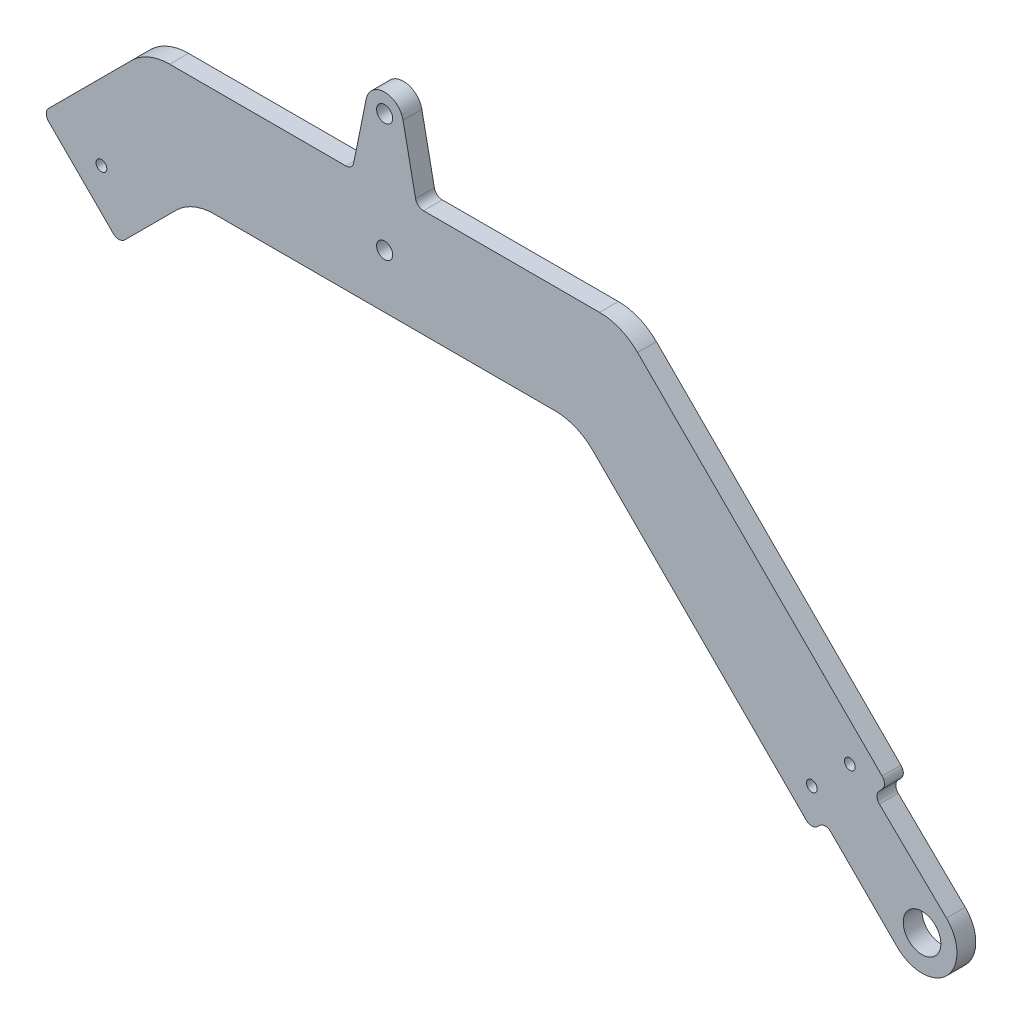
SolidWorks part; units mm, degrees
ref_plane "Front Plane" through (0, 0, 0) normal (0, 0, 1) x (1, 0, 0)
ref_plane "Top Plane" through (0, 0, 0) normal (0, 1, 0) x (1, 0, 0)
ref_plane "Right Plane" through (0, 0, 0) normal (1, 0, 0) x (0, 0, -1)
sketch "Sketch2" plane through (0, 0, 0) normal (0, 0, 1) x (1, 0, 0)
  line L0 (-100, 0) -> (100, 0) construction
  line L1 (-100, 0) -> (0, 100) construction
  line L2 (0, 100) -> (100, 0) construction
  line L3 (0, 0) -> (-52.6991, 47.3009) construction
  line L4 (-40, 60) -> (40, 60) construction
  line L5 (0, 100) -> (0, 60) construction
  circle A0 centre (-100, 0) radius 20
  circle A1 centre (0, 0) radius 20
  circle A2 centre (100, 0) radius 20
  point P2 (0, 0)
  dimension "D5" = 40
  dimension "D1" = 200
  dimension "D2" = 93.09
  dimension "D3" = 80
  dimension "D4" = 90
sketch "Sketch3" plane through (0, 0, 0) normal (0, 0, 1) x (1, 0, 0)
  line L0 (-40, 60) -> (-56.5165, 43.4835) construction
  line L1 (75.9584, 9.8995) -> (90.1005, 24.0416) construction
  line L2 (-40, 60) -> (40, 60) construction
  line L3 (40, 60) -> (86.565, 13.435) construction
  line L4 (0, 100) -> (100, 0) construction
  line L5 (86.565, 13.435) -> (40, 60) construction
  line L6 (-100, 0) -> (0, 100) construction
  line L7 (44.1421, 70) -> (93.636, 20.5061)
  line L8 (-44.1421, 70) -> (44.1421, 70)
  line L9 (-44.1421, 70) -> (-63.5876, 50.5546)
  line L10 (35.8579, 50) -> (79.4939, 6.364)
  line L11 (-35.8579, 50) -> (35.8579, 50)
  line L12 (-35.8579, 50) -> (-49.4454, 36.4124)
  line L13 (-63.5876, 50.5546) -> (-49.4454, 36.4124)
  line L14 (79.4939, 6.364) -> (93.636, 20.5061)
  line L15 (81.9688, 8.8388) -> (95.4038, -4.5962)
  line L16 (90.9809, 17.8509) -> (104.534, 4.6576)
  line L17 (-3.4304, 82.6944) -> (-6, 70)
  line L18 (0, 100) -> (0, 60) construction
  line L19 (3.4304, 82.6944) -> (6, 70)
  circle A0 centre (100, 0) radius 3.5
  circle A1 centre (100, 0) radius 10 construction
  arc A2 (95.4038, -4.5962) -> (104.534, 4.6576) centre (100, 0) ccw
  circle A3 centre (100, 0) radius 0.5
  circle A4 centre (100, 0) radius 20 construction
  circle A5 centre (100, 0) radius 6.5 construction
  circle A6 centre (79.4939, 13.435) radius 1
  circle A7 centre (86.565, 20.5061) radius 1
  circle A8 centre (0, 60) radius 1.5
  circle A11 centre (0, 82) radius 1.5
  arc A12 (3.4304, 82.6944) -> (-3.4304, 82.6944) centre (0, 82) ccw
  circle A13 centre (0, 82) radius 3.5 construction
  circle A14 centre (-52.6991, 47.3009) radius 1
  dimension "D4" = 20
  dimension "D5" = 7
  dimension "D10" = 2
  dimension "D11" = 3
  dimension "D15" = 2
  dimension "D3" = 27.5
  dimension "D8" = 19
  dimension "D9" = 5
  dimension "D12" = 2
  dimension "D14" = 6
  dimension "D13" = 6
  dimension "D16" = 5
  dimension "D17" = 5
  dimension "D18" = 12
  dimension "D1" = 10
  dimension "D2" = 10
  dimension "D6" = 3
  dimension "D7" = 3
sketch "Sketch4" plane through (0, 0, 0) normal (0, 0, 1) x (1, 0, 0)
  line L0 (-100, 0) -> (100, 0) construction
  line L1 (-88.5703, 11.4297) -> (-52.6991, 47.3009) construction
  line L2 (-100, 0) -> (0, 100) construction
  line L3 (-52.6991, 47.3009) -> (-14.1397, 12.6913) construction
  line L4 (0, 0) -> (-52.6991, 47.3009) construction
  line L5 (-79.4939, 6.364) -> (-52.3277, 33.5302)
  line L6 (-52.3277, 33.5302) -> (-20.8193, 5.2493)
  line L7 (-93.636, 20.5061) -> (-53.0706, 61.0716)
  line L8 (-53.0706, 61.0716) -> (-7.4601, 20.1332)
  line L9 (-95.6414, 18.5007) -> (-53.0706, 61.0716) construction
  line L10 (-81.4993, 4.3586) -> (-52.3277, 33.5302) construction
  line L11 (-7.4601, 20.1332) -> (-20.8193, 5.2493)
  line L13 (-79.4939, 6.364) -> (-93.636, 20.5061)
  line L14 (-91.1612, 18.0312) -> (-104.5962, 4.5962)
  line L15 (-81.9688, 8.8388) -> (-95.4038, -4.5962)
  line L16 (-9.9683, 17.3388) -> (4.2763, 4.8952)
  line L17 (-18.4815, 7.854) -> (-4.3418, -4.8373)
  line L18 (9.9995, -0.1043) -> (10.0659, -0.1623)
  line L19 (-85.2086, 28.9335) -> (-71.0665, 14.7914) construction
  line L20 (-25.2845, 9.2571) -> (-11.9252, 24.141) construction
  circle A0 centre (-100, 0) radius 10 construction
  circle A1 centre (0, 0) radius 10 construction
  circle A6 centre (-100, 0) radius 3.5
  circle A7 centre (0, 0) radius 3.5
  arc A8 (-104.5962, 4.5962) -> (-95.4038, -4.5962) centre (-100, 0) ccw
  arc A9 (-4.3418, -4.8373) -> (4.2763, 4.8952) centre (0, 0) ccw
  circle A10 centre (0, 0) radius 20 construction
  circle A11 centre (0, 0) radius 6.5 construction
  circle A12 centre (-100, 0) radius 6.5 construction
  circle A13 centre (-81.6731, 25.398) radius 1
  circle A14 centre (-74.602, 18.3269) radius 1
  circle A15 centre (-21.9447, 12.9781) radius 1
  circle A16 centre (-15.2651, 20.42) radius 1
  dimension "D1" = 20
  dimension "D2" = 7
  dimension "D10" = 5
  dimension "D13" = 2
  dimension "D7" = 19
  dimension "D8" = 19
  dimension "D9" = 5
  dimension "D11" = 5
  dimension "D12" = 5
  dimension "D14" = 6
  dimension "D3" = 3
  dimension "D4" = 3
  dimension "D5" = 10
  dimension "D6" = 10
sketch "Sketch5" plane through (0, 0, 0) normal (0, 0, 1) x (1, 0, 0)
  line L13 (-44.1421, 70) -> (44.1421, 70)
  line L14 (44.1421, 70) -> (57.8914, 80.5)
  line L16 (57.8914, 80.5) -> (57.8914, 90.5)
  line L17 (57.8914, 90.5) -> (-57.1086, 90.5)
  line L18 (-57.1086, 90.5) -> (-57.1086, 80.5)
  line L19 (-57.1086, 80.5) -> (-44.1421, 70)
  line L20 (-4, 60) -> (-4, 70)
  line L21 (4, 60) -> (4, 70)
  line L22 (-22.5, 82) -> (22.5, 82) construction
  line L23 (0, 100) -> (0, 60) construction
  line L24 (-22.5, 86.5) -> (22.5, 86.5)
  line L25 (-22.5, 77.5) -> (22.5, 77.5)
  circle A0 centre (0, 60) radius 1.5 construction
  circle A1 centre (0, 60) radius 1.5
  arc A2 (-4, 60) -> (4, 60) centre (0, 60) ccw
  circle A3 centre (0, 60) radius 4 construction
  arc A4 (-22.5, 86.5) -> (-22.5, 77.5) centre (-22.5, 82) ccw
  arc A5 (22.5, 77.5) -> (22.5, 86.5) centre (22.5, 82) ccw
  point P21 (0, 82)
  dimension "D1" = 115
  dimension "D2" = 10
  dimension "D3" = 2.5
  dimension "D4" = 45
  dimension "D5" = 9
  dimension "D6" = 4
  dimension "D7" = 141
sketch "Sketch7" plane through (0, 0, 0) normal (0, 0, 1) x (1, 0, 0)
  line L0 (81.9688, 8.8388) -> (95.4038, -4.5962) construction
  line L1 (90.9809, 17.8509) -> (104.534, 4.6576) construction
  line L2 (-3.4304, 82.6944) -> (-6, 70) construction
  line L3 (3.4304, 82.6944) -> (6, 70) construction
  line L4 (81.9688, 8.8388) -> (95.4038, -4.5962)
  line L5 (90.9809, 17.8509) -> (104.534, 4.6576)
  line L6 (-3.4304, 82.6944) -> (-6, 70)
  line L7 (3.4304, 82.6944) -> (6, 70)
  line L8 (-49.4454, 36.4124) -> (-35.8579, 50)
  line L9 (-63.5876, 50.5546) -> (-49.4454, 36.4124)
  line L10 (-44.1421, 70) -> (-63.5876, 50.5546)
  line L11 (44.1421, 70) -> (-44.1421, 70)
  line L12 (93.636, 20.5061) -> (44.1421, 70)
  line L13 (79.4939, 6.364) -> (93.636, 20.5061)
  line L14 (35.8579, 50) -> (79.4939, 6.364)
  line L15 (-35.8579, 50) -> (35.8579, 50)
  line L16 (-49.4454, 36.4124) -> (-35.8579, 50)
  line L17 (-63.5876, 50.5546) -> (-49.4454, 36.4124)
  line L18 (-44.1421, 70) -> (-63.5876, 50.5546)
  line L19 (44.1421, 70) -> (6, 70)
  line L20 (93.636, 20.5061) -> (44.1421, 70)
  line L21 (79.4939, 6.364) -> (81.9688, 8.8388)
  line L22 (35.8579, 50) -> (79.4939, 6.364)
  line L23 (-35.8579, 50) -> (35.8579, 50)
  line L24 (90.9809, 17.8509) -> (93.636, 20.5061)
  line L25 (-6, 70) -> (-44.1421, 70)
  arc A0 (95.4038, -4.5962) -> (104.534, 4.6576) centre (100, 0) ccw construction
  circle A1 centre (100, 0) radius 0.5
  circle A2 centre (100, 0) radius 0.5
  circle A3 centre (100, 0) radius 3.5
  circle A4 centre (100, 0) radius 3.5
  circle A5 centre (0, 82) radius 1.5
  circle A6 centre (0, 82) radius 1.5
  circle A7 centre (0, 60) radius 1.5
  circle A8 centre (0, 60) radius 1.5
  circle A9 centre (86.565, 20.5061) radius 1
  circle A10 centre (86.565, 20.5061) radius 1
  circle A11 centre (79.4939, 13.435) radius 1
  circle A12 centre (79.4939, 13.435) radius 1
  circle A13 centre (-52.6991, 47.3009) radius 1
  circle A14 centre (-52.6991, 47.3009) radius 1
  arc A15 (3.4304, 82.6944) -> (-3.4304, 82.6944) centre (0, 82) ccw construction
  arc A16 (95.4038, -4.5962) -> (104.534, 4.6576) centre (100, 0) ccw
  arc A17 (3.4304, 82.6944) -> (-3.4304, 82.6944) centre (0, 82) ccw
  dimension "D1" = 0
  dimension "D2" = 0
  dimension "D3" = 0
  dimension "D4" = 0
  dimension "D5" = 0
  dimension "D6" = 0
  dimension "D7" = 0
  dimension "D8" = 0
extrude "Boss-Extrude2" add sketch "Sketch7" along normal blind 3.5 contours L7 A17 L6 L25 L18 L17 L16 L23 L22 L21 L4 A16 L5 L24 L20 L19 A4 A6 A8 A10 A12 A14
fillet "Fillet1" radius 10 4 edges at (35.8579, 50, 1.75) (-35.8579, 50, 1.75) (-44.1421, 70, 1.75) (44.1421, 70, 1.75)
fillet "Fillet2" radius 1.5 8 edges at (-49.4454, 36.4124, 1.75) (-63.5876, 50.5546, 1.75) (-6, 70, 1.75) (6, 70, 1.75) (90.9809, 17.8509, 1.75) (93.636, 20.5061, 1.75) (81.9688, 8.8388, 1.75) (79.4939, 6.364, 1.75)
